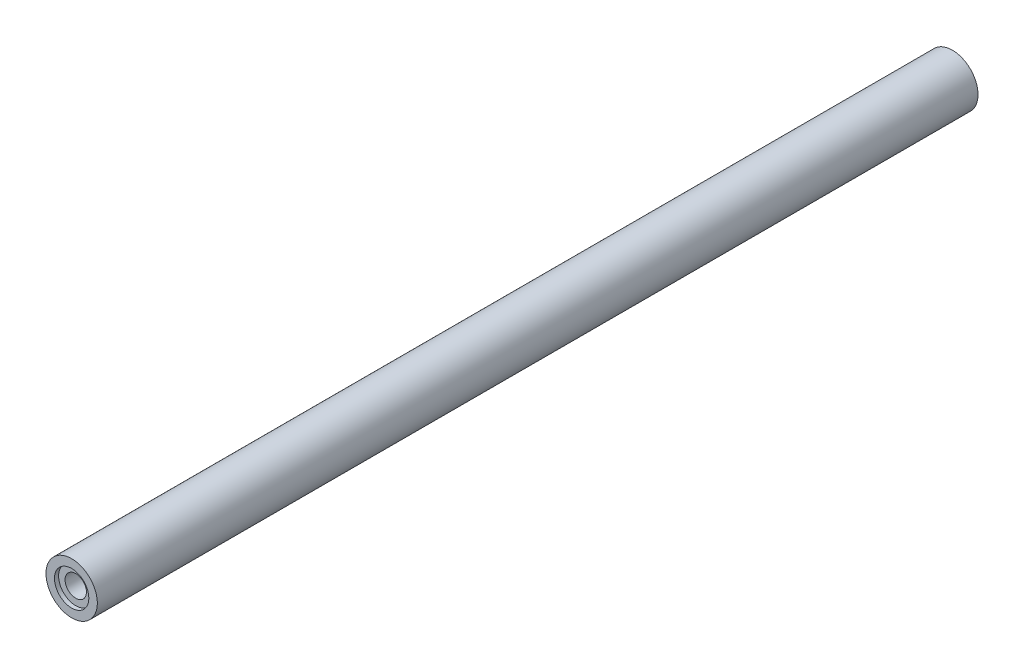
SolidWorks part; units mm, degrees
material "6061 Alloy"
ref_plane "Front" through (0, 0, 0) normal (0, 0, 1) x (1, 0, 0)
ref_plane "Top" through (0, 0, 0) normal (0, 1, 0) x (1, 0, 0)
ref_plane "Right" through (0, 0, 0) normal (1, 0, 0) x (0, 0, -1)
sketch "Sketch1" plane through (0, 0, 0) normal (0, 0, 1) x (1, 0, 0)
  circle A0 centre (0, 0) radius 9.525
  dimension "D1" = 19.05
extrude "Boss-Extrude1" add sketch "Sketch1" along normal blind 327.025
sketch "Sketch2" plane through (0, 0, 327.025) normal (0, 0, 1) x (1, 0, 0)
  circle A0 centre (0, 0) radius 6.3754
  dimension "D1" = 12.7508
extrude "Cut-Extrude1" cut sketch "Sketch2" against normal blind 1.524
hole_wizard "3/8-16 Tapped Hole1" positions "Sketch3" profile "Sketch4" tap size "3/8-16" standard "ANSI Inch"
sketch "Sketch3" plane through (0, 0, 325.501) normal (0, 0, 1) x (1, 0, 0)
  point P0 (0, 0)
sketch "Sketch4" plane through (0, 0, 325.501) normal (1, 0, 0) x (0, -1, 0)
  line L0 (0, 0) -> (0, 27.7847)
  line L1 (0, 27.7847) -> (3.9687, 25.4)
  line L2 (3.9687, 25.4) -> (3.9687, 0)
  line L5 (3.9687, 0) -> (0, 0)
  line L10 (0, 27.7847) -> (-3.9688, 25.4) construction
  line L11 (0, -6.35) -> (0, 107.95) construction
  dimension "Tap Drill Dia." = 7.9375
  dimension "Tap Drill Depth" = 25.4
  dimension "Drill Angle" = 118
cosmetic thread "Hole Thread1" parameters "D1"=19.05, "D2"=9.525
sketch "Sketch5" plane through (0, 0, 0) normal (0, 0, -1) x (-1, 0, 0)
  circle A0 centre (0, 0) radius 6.3754
  dimension "D1" = 12.7508
extrude "Cut-Extrude2" cut sketch "Sketch5" against normal blind 1.524
hole_wizard "3/8-16 Tapped Hole2" positions "Sketch6" profile "Sketch7" tap size "3/8-16" standard "ANSI Inch"
sketch "Sketch6" plane through (0, 0, 1.524) normal (0, 0, -1) x (-1, 0, 0)
  point P0 (0, 0)
sketch "Sketch7" plane through (0, 0, 1.524) normal (1, 0, 0) x (0, 1, 0)
  line L0 (0, 0) -> (0, 27.7847)
  line L1 (0, 27.7847) -> (3.9687, 25.4)
  line L2 (3.9687, 25.4) -> (3.9687, 0)
  line L5 (3.9687, 0) -> (0, 0)
  line L10 (0, 27.7847) -> (-3.9687, 25.4) construction
  line L11 (0, -6.35) -> (0, 107.95) construction
  dimension "Tap Drill Dia." = 7.9375
  dimension "Tap Drill Depth" = 25.4
  dimension "Drill Angle" = 118
cosmetic thread "Hole Thread2" parameters "D1"=19.05, "D2"=9.525
